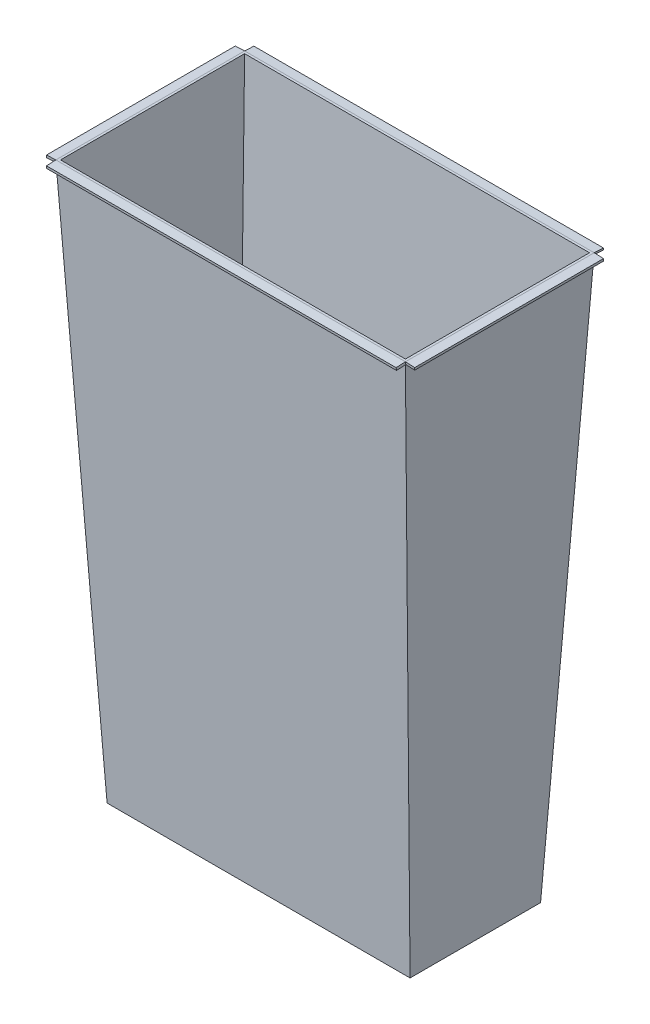
SolidWorks part; units mm, degrees
ref_plane "Front Plane" through (0, 0, 0) normal (0, 0, 1) x (1, 0, 0)
ref_plane "Top Plane" through (0, 0, 0) normal (0, 1, 0) x (1, 0, 0)
ref_plane "Right Plane" through (0, 0, 0) normal (1, 0, 0) x (0, 0, -1)
sketch "Sketch1" plane through (0, 0, 0) normal (0, 1, 0) x (1, 0, 0)
  line L0 (0, 0) -> (0, 282.575)
  line L1 (0, 282.575) -> (501.65, 282.575)
  line L2 (501.65, 282.575) -> (501.65, 0)
  line L3 (501.65, 0) -> (0, 0)
  line L4 (12.7, 269.875) -> (12.7, 12.7)
  line L5 (12.7, 12.7) -> (488.95, 12.7)
  line L6 (488.95, 12.7) -> (488.95, 269.875)
  line L7 (488.95, 269.875) -> (12.7, 269.875)
  dimension "D1" = 282.575
  dimension "D2" = 501.65
  dimension "D3" = 12.7
  dimension "D4" = 12.7
  dimension "D5" = 12.7
  dimension "D6" = 12.7
ref_plane "Plane1" through (0, -762, 0) normal (0, 1, 0) x (1, 0, 0)
sketch "Sketch6" plane through (0, -762, 0) normal (0, 1, 0) x (1, 0, 0)
  line L0 (0, 0) -> (450.85, 0) construction
  line L1 (44.45, 50.8) -> (457.2, 50.8)
  line L2 (44.45, 228.6) -> (457.2, 228.6)
  line L3 (0, 228.6) -> (0, 0) construction
  line L4 (44.45, 228.6) -> (44.45, 50.8)
  line L5 (457.2, 228.6) -> (457.2, 50.8)
  dimension "D1" = 44.45
  dimension "D2" = 177.8
  dimension "D3" = 412.75
  dimension "D5" = 50.8
loft "Loft1" add profiles "Sketch1", "Sketch6"
shell "Shell2" thickness 3.175
sketch "Sketch7" plane through (12.678, 0.5282, 0) normal (-0.9991, -0.0416, 0) x (0, 0, 1)
  line L0 (-269.875, -0.5287) -> (-12.7, -0.5287)
  line L1 (-12.7, -0.5287) -> (-12.7, -3.7037)
  line L2 (-12.7, -3.7037) -> (-269.7032, -3.7037)
  line L3 (-269.875, -0.5287) -> (-228.6, -763.1899) construction
  line L4 (-269.875, -0.5287) -> (-269.7032, -3.7037)
  dimension "D1" = 3.175
extrude "Boss-Extrude3" add sketch "Sketch7" along normal blind 12.7
sketch "Sketch8" plane through (0, -14.5755, -269.0855) normal (0, -0.0541, -0.9985) x (-1, 0, 0)
  line L0 (-12.7, 14.5968) -> (-488.95, 14.5968)
  line L1 (-488.95, 14.5968) -> (-488.8465, 12.1087)
  line L2 (-488.95, 14.5968) -> (-457.2, -748.5202) construction
  line L3 (-488.8465, 12.1087) -> (-12.8035, 12.1087)
  line L4 (-12.8322, 11.4199) -> (-44.45, -748.5202) construction
  line L5 (0, 15.2837) -> (-501.65, 15.2837) construction
  arc A0 (-12.8035, 12.1087) -> (-12.7, 14.5968) centre (17.1491, 12.1087) cw
  dimension "D1" = 3.175
extrude "Boss-Extrude4" add sketch "Sketch8" along normal blind 12.7
sketch "Sketch9" plane through (488.1026, -20.3376, 0) normal (0.9991, -0.0416, 0) x (0, 0, -1)
  line L0 (12.7, 20.3553) -> (269.875, 20.3553)
  line L1 (269.875, 20.3553) -> (269.7032, 17.1803)
  line L2 (269.7404, 17.8687) -> (228.6, -742.3059) construction
  line L3 (269.7032, 17.1803) -> (12.8586, 17.1803)
  line L4 (12.7, 20.3553) -> (50.8, -742.3059) construction
  line L5 (12.8586, 17.1803) -> (12.7, 20.3553)
  dimension "D1" = 3.175
extrude "Boss-Extrude5" add sketch "Sketch9" along normal blind 12.7
sketch "Sketch10" plane through (0, 0.6334, -12.6683) normal (0, -0.0499, 0.9988) x (1, 0, 0)
  line L0 (12.7, -0.6342) -> (488.95, -0.6342)
  line L1 (488.95, -0.6342) -> (489.3544, -3.8092)
  line L2 (488.8178, -16.6366) -> (457.2, -772.465) construction
  line L3 (489.3544, -3.8092) -> (12.8321, -3.8092)
  line L4 (12.8322, -3.8104) -> (44.45, -763.5861) construction
  line L5 (12.8321, -3.8092) -> (12.7, -0.6342)
  dimension "D1" = 3.175
extrude "Boss-Extrude6" add sketch "Sketch10" along normal blind 12.7
sketch "Sketch11" plane through (0.8474, 20.3376, 0) normal (0.0416, 0.9991, 0) x (0.9991, -0.0416, 0)
  line L0 (493.2811, 246.2875) -> (493.2811, 36.2875) construction
  line L1 (501.2151, 282.575) -> (501.2151, 0) construction
  line L2 (485.3511, 15.879) -> (485.3511, 266.6953) construction
  line L3 (508.1746, 208.5975) -> (508.1746, 73.9775) construction
  line L4 (493.2811, 141.2875) -> (508.1746, 141.2875) construction
  line L5 (493.2811, 229.2875) -> (493.2811, 224.7875) construction
  circle A0 centre (493.2811, 19.2875) radius 2
  circle A1 centre (493.2811, 53.2875) radius 2
  circle A2 centre (493.2811, 263.2875) radius 2
  circle A3 centre (493.2811, 229.2875) radius 2
  point P2 (493.2811, 141.2875)
  point P5 (501.2151, 141.2875)
  point P20 (508.1746, 141.2875)
  point P23 (0, 0)
  dimension "D1" = 4
  dimension "D5" = 4
  dimension "D2" = 7.93
  dimension "D3" = 17
  dimension "D4" = 210
  dimension "D6" = 17
  dimension "D7" = 134.62
  dimension "D8" = 4.5
